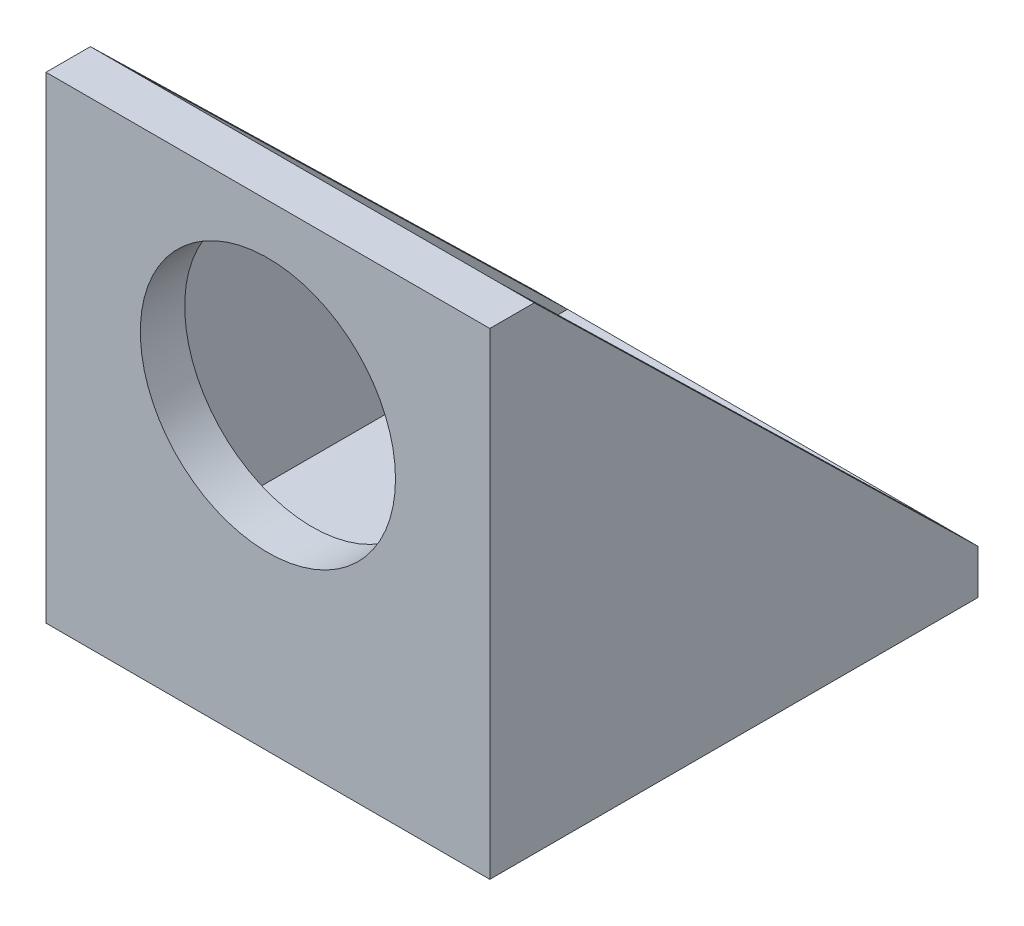
SolidWorks part; units mm, degrees
ref_plane "前视基准面" through (0, 0, 0) normal (0, 0, 1) x (1, 0, 0)
ref_plane "上视基准面" through (0, 0, 0) normal (0, 1, 0) x (1, 0, 0)
ref_plane "右视基准面" through (0, 0, 0) normal (1, 0, 0) x (0, 0, -1)
sketch "草图1" plane through (0, 0, 0) normal (0, 0, 1) x (1, 0, 0)
  line L1 (-17, -25.5) -> (17, -25.5)
  line L2 (-17, -25.5) -> (-17, 25.5)
  line L3 (-17, 25.5) -> (17, 25.5)
  line L4 (17, -25.5) -> (17, 25.5)
  line L5 (-17, -25.5) -> (17, 25.5) construction
  line L6 (-17, 25.5) -> (17, -25.5) construction
  point P0 (0, 0)
  dimension "D1" = 34
  dimension "D2" = 51
extrude "凸台-拉伸1" add sketch "草图1" along normal blind 4
sketch "草图2" plane through (0, 0, 4) normal (0, 0, 1) x (1, 0, 0)
  line L0 (-17, -25.5) -> (17, -25.5) construction
  line L1 (0, -25.5) -> (0, 4.2077) construction
  circle A2 centre (0, -2.5) radius 11.5
  dimension "D5" = 23
extrude "切除-拉伸1" cut sketch "草图2" against normal through all
sketch "草图5" plane through (0, -25.5, 0) normal (0, -1, 0) x (1, 0, 0)
  line L0 (0, 4) -> (0, 0) construction
  line L1 (-17, 4) -> (17, 4) construction
  line L7 (17, 0) -> (-17, 0)
  line L8 (17, 0) -> (17, 15)
  line L9 (17, 15) -> (-17, 15)
  line L10 (-17, 0) -> (-17, 15)
  point P5 (0, 2)
  dimension "D1" = 15
  dimension "D2" = 34
extrude "凸台-拉伸2" add sketch "草图5" along normal blind 4
sketch "草图6" plane through (0, -29.5, 0) normal (0, -1, 0) x (1, 0, 0)
  line L0 (0, 0) -> (0, 7.5) construction
  line L3 (0, 7.5) -> (13, 7.5) construction
  circle A4 centre (13, 7.5) radius 1.5
  circle A5 centre (-13, 7.5) radius 1.5
  point P6 (0, 2)
  dimension "D3" = 3
  dimension "D1" = 7.5
  dimension "D2" = 13
extrude "切除-拉伸3" cut sketch "草图6" against normal blind 4
sketch "草图9" plane through (0, -25.5, 0) normal (0, 1, 0) x (1, 0, 0)
  line L0 (0, -15) -> (0, -4) construction
  line L1 (17, -15) -> (-17, -15) construction
  line L2 (17, -4) -> (-17, -4) construction
  line L3 (0, -15) -> (10, -15) construction
  line L4 (0, -15) -> (-10, -15) construction
  line L6 (-10, -15) -> (-7, -15)
  line L7 (-10, -15) -> (-10, -4)
  line L8 (-10, -4) -> (-7, -4)
  line L9 (-7, -15) -> (-7, -4)
  line L10 (10, -15) -> (7, -15)
  line L11 (10, -15) -> (10, -4)
  line L12 (10, -4) -> (7, -4)
  line L13 (7, -15) -> (7, -4)
  line L14 (-17, -4) -> (17, -4) construction
  dimension "D1" = 10
  dimension "D2" = 10
  dimension "D3" = 11
  dimension "D4" = 3
  dimension "D5" = 11
  dimension "D6" = 3
sketch "草图12" plane through (0, 25.5, 0) normal (0, 1, 0) x (1, 0, 0)
  line L4 (17, 0) -> (-17, 0)
  line L5 (-17, 0) -> (-17, -4)
  line L6 (-17, -4) -> (17, -4)
  line L7 (17, -4) -> (17, 0)
  line L8 (17, 0) -> (-17, 0)
  line L9 (-17, 0) -> (-17, -4)
  line L10 (-17, -4) -> (17, -4)
  line L11 (17, -4) -> (17, 0)
  dimension "D1" = 0
extrude "切除-拉伸5" cut sketch "草图12" against normal blind 5
sketch "草图13" plane through (0, 20.5, 0) normal (0, 1, 0) x (1, 0, 0)
  line L4 (17, -4) -> (17, 0)
  line L5 (17, 0) -> (-17, 0)
  line L6 (-17, 0) -> (-17, -4)
  line L7 (-17, -4) -> (17, -4)
  line L8 (17, -4) -> (17, 0)
  line L9 (17, 0) -> (-17, 0)
  line L10 (-17, 0) -> (-17, -4)
  line L11 (-17, -4) -> (17, -4)
  dimension "D1" = 0
extrude "切除-拉伸6" cut sketch "草图13" against normal blind 7
sketch "草图14" plane through (0, 0, 15) normal (0, 0, 1) x (1, 0, 0)
  line L4 (17, -25.5) -> (-17, -25.5)
  line L5 (-17, -25.5) -> (-17, -29.5)
  line L6 (-17, -29.5) -> (17, -29.5)
  line L7 (17, -29.5) -> (17, -25.5)
  line L8 (17, -25.5) -> (-17, -25.5)
  line L9 (-17, -25.5) -> (-17, -29.5)
  line L10 (-17, -29.5) -> (17, -29.5)
  line L11 (17, -29.5) -> (17, -25.5)
  dimension "D1" = 0
extrude "凸台-拉伸3" add sketch "草图14" along normal blind 33
sketch "草图15" plane through (0, -25.5, 0) normal (0, 1, 0) x (1, 0, 0)
  line L0 (-13, -7.5) -> (-13, -40.5) construction
  line L1 (-13, -7.5) -> (13, -7.5) construction
  line L2 (13, -7.5) -> (13, -40.5) construction
  circle A0 centre (13, -40.5) radius 1.75
  circle A1 centre (-13, -40.5) radius 1.75
  dimension "D2" = 3.5
  dimension "D3" = 3.5
  dimension "D1" = 33
extrude "切除-拉伸7" cut sketch "草图15" against normal blind 44
sketch "草图16" plane through (-17, 0, 0) normal (-1, 0, 0) x (0, 0, 1)
  line L0 (4, -25.5) -> (4, -6)
  line L2 (4, 13.5) -> (4, -25.5) construction
  line L3 (4, -25.5) -> (24, -25.5) construction
  line L4 (48, -25.5) -> (4, -25.5) construction
  line L5 (4, -6) -> (24, -25.5)
  line L6 (24, -25.5) -> (4, -25.5)
  dimension "D1" = 19.5
  dimension "D2" = 20
extrude "凸台-拉伸4" add sketch "草图16" against normal blind 3
sketch "草图17" plane through (17, 0, 0) normal (1, 0, 0) x (0, 0, -1)
  line L0 (-24, -25.5) -> (-4, -6) construction
  line L1 (-24, -25.5) -> (-4, -6)
  line L2 (-24, -25.5) -> (-4, -25.5)
  line L3 (-4, -25.5) -> (-4, -6)
extrude "凸台-拉伸5" add sketch "草图17" against normal blind 3
sketch "草图18" plane through (0, -25.5, 0) normal (0, 1, 0) x (1, 0, 0)
  line L3 (20.499, -32.5) -> (17, -24)
  line L4 (-20.501, -32.5) -> (-17, -24)
  line L5 (-17, -24) -> (17, -24)
  line L6 (20.499, -32.5) -> (20.499, -40.5)
  line L7 (10.999, -50) -> (-11.001, -50)
  line L8 (-20.501, -40.5) -> (-20.501, -32.5)
  circle A2 centre (-13, -40.5) radius 1.75
  circle A3 centre (13, -40.5) radius 1.75
  arc A4 (10.999, -50) -> (20.499, -40.5) centre (10.999, -40.5) ccw
  arc A5 (-20.501, -40.5) -> (-11.001, -50) centre (-11.001, -40.5) ccw
extrude "凸台-拉伸6" add sketch "草图18" against normal blind 4
sketch "草图19" plane through (0, -25.5, 0) normal (0, 1, 0) x (1, 0, 0)
  line L0 (-20.501, -32.5) -> (-17.501, -32.5)
  line L1 (-17.501, -32.5) -> (-14, -24)
  line L3 (-17, -24) -> (-20.501, -32.5)
  line L5 (17, -24) -> (20.499, -32.5)
  line L6 (20.499, -32.5) -> (17.499, -32.5)
  line L7 (17.499, -32.5) -> (14, -24)
  line L8 (-17, -24) -> (-17, -16)
  line L9 (-17, -24) -> (-17, -4) construction
  line L10 (-17, -16) -> (-14, -16)
  line L11 (-14, -8.618) -> (-14, -24) construction
  line L12 (-14, -16) -> (-14, -24)
  line L13 (14, -24) -> (14, -16)
  line L14 (14, -16) -> (17, -16)
  line L15 (17, -4) -> (17, -24) construction
  line L16 (17, -16) -> (17, -24)
  dimension "D1" = 3
  dimension "D2" = 3
  dimension "D3" = 8
extrude "凸台-拉伸7" add sketch "草图19" along normal blind 5
sketch "草图20" plane through (0, 0, 4) normal (0, 0, 1) x (1, 0, 0)
  line L1 (-31.7552, -43.9) -> (31.7552, -43.9)
  line L2 (-31.7552, -43.9) -> (-31.7552, 28.3859)
  line L3 (-31.7552, 28.3859) -> (31.7552, 28.3859)
  line L4 (31.7552, -43.9) -> (31.7552, 28.3859)
  line L5 (-31.7552, -43.9) -> (31.7552, 28.3859) construction
  line L6 (-31.7552, 28.3859) -> (31.7552, -43.9) construction
  point P0 (0, -7.757)
extrude "切除-拉伸10" cut sketch "草图20" along normal blind 67
sketch "草图21" plane through (17, 0, 0) normal (1, 0, 0) x (0, 0, -1)
  line L4 (-4, 13.5) -> (-4, -29.5)
  line L5 (-4, -29.5) -> (0, -29.5)
  line L6 (0, -29.5) -> (0, 13.5)
  line L7 (0, 13.5) -> (-4, 13.5)
  line L8 (-4, 13.5) -> (-4, -29.5)
  line L9 (-4, -29.5) -> (0, -29.5)
  line L10 (0, -29.5) -> (0, 13.5)
  line L11 (0, 13.5) -> (-4, 13.5)
  dimension "D1" = 0
extrude "凸台-拉伸8" add sketch "草图21" along normal blind 3
sketch "草图22" plane through (-17, 0, 0) normal (-1, 0, 0) x (0, 0, 1)
  line L4 (0, -29.5) -> (4, -29.5)
  line L5 (4, -29.5) -> (4, 13.5)
  line L6 (4, 13.5) -> (0, 13.5)
  line L7 (0, 13.5) -> (0, -29.5)
  line L8 (0, -29.5) -> (4, -29.5)
  line L9 (4, -29.5) -> (4, 13.5)
  line L10 (4, 13.5) -> (0, 13.5)
  line L11 (0, 13.5) -> (0, -29.5)
  dimension "D1" = 0
extrude "凸台-拉伸9" add sketch "草图22" along normal blind 3
sketch "草图23" plane through (0, 0, 0) normal (0, 0, -1) x (-1, 0, 0)
  line L1 (-20, -29.5) -> (20, -29.5)
  line L2 (-20, -29.5) -> (-20, -25.5)
  line L3 (-20, -25.5) -> (20, -25.5)
  line L4 (20, -29.5) -> (20, -25.5)
  line L5 (20, 13.5) -> (20, -29.5) construction
  dimension "D1" = 4
  dimension "D2" = 40
extrude "凸台-拉伸10" add sketch "草图23" along normal blind 40
sketch "草图24" plane through (0, 0, 0) normal (0, 0, -1) x (-1, 0, 0)
  line L1 (20, 13.5) -> (17, 13.5)
  line L2 (20, 13.5) -> (20, -25.5)
  line L3 (20, -25.5) -> (17, -25.5)
  line L4 (17, 13.5) -> (17, -25.5)
  line L5 (20, -25.5) -> (-20, -25.5) construction
  line L6 (0, 13.5) -> (0, -25.5) construction
  line L7 (-20, 13.5) -> (20, 13.5) construction
  line L8 (20, -25.5) -> (-20, -25.5) construction
  line L9 (-17, 13.5) -> (-17, -25.5)
  line L10 (-20, -25.5) -> (-17, -25.5)
  line L11 (-20, 13.5) -> (-20, -25.5)
  line L12 (-20, 13.5) -> (-17, 13.5)
  dimension "D1" = 39
  dimension "D2" = 3
extrude "凸台-拉伸11" add sketch "草图24" along normal blind 40
sketch "草图25" plane through (-17, 0, 0) normal (1, 0, 0) x (0, 0, -1)
  line L0 (0, 13.5) -> (40, -25.5)
  line L1 (40, -25.5) -> (40, 13.5)
  line L2 (40, 13.5) -> (0, 13.5)
extrude "切除-拉伸11" cut sketch "草图25" against normal mid plane 145
sketch "草图26" plane through (0, -25.5, 0) normal (0, 1, 0) x (1, 0, 0)
  line L0 (-17, 20) -> (17, 20) construction
  line L1 (-17, 40) -> (-17, 0) construction
  line L2 (17, 0) -> (17, 40) construction
  line L4 (-12.5, 8) -> (12.5, 8) construction
  line L5 (-12.5, 8) -> (-12.5, 32) construction
  line L6 (-12.5, 32) -> (12.5, 32) construction
  line L7 (12.5, 8) -> (12.5, 32) construction
  line L8 (-12.5, 8) -> (12.5, 32) construction
  line L9 (-12.5, 32) -> (12.5, 8) construction
  circle A0 centre (-12.5, 32) radius 1.75
  circle A1 centre (12.5, 32) radius 1.75
  circle A2 centre (12.5, 8) radius 1.75
  circle A3 centre (-12.5, 8) radius 1.75
  point P6 (0, 20)
  dimension "D3" = 3.5
  dimension "D4" = 3.5
  dimension "D5" = 3.5
  dimension "D6" = 3.5
  dimension "D1" = 24
  dimension "D2" = 25
extrude "切除-拉伸12" cut sketch "草图26" against normal blind 5
